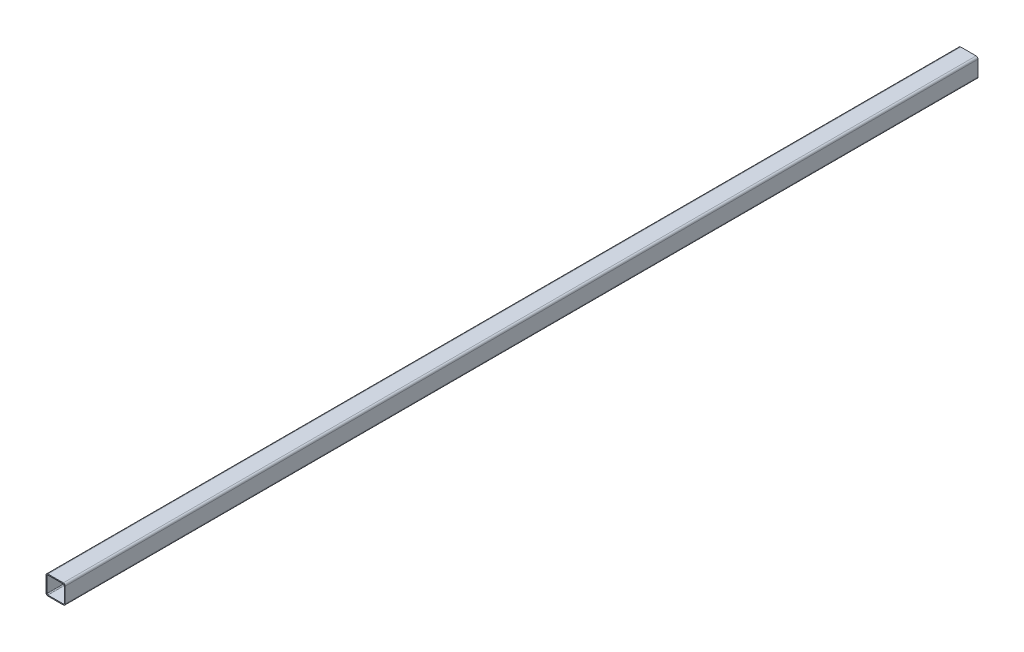
SolidWorks part; units mm, degrees
material "1.4305 (X8CrNiS18-9)"
ref_plane "Ön Düzlem" through (0, 0, 0) normal (0, 0, 1) x (1, 0, 0)
ref_plane "Üst Düzlem" through (0, 0, 0) normal (0, 1, 0) x (1, 0, 0)
ref_plane "Sağ Düzlem" through (0, 0, 0) normal (1, 0, 0) x (0, 0, -1)
sketch "Çizim1" plane through (0, 0, 0) normal (0, 0, 1) x (1, 0, 0)
  line L0 (-18, 16) -> (-18, -16)
  line L1 (-16, 20) -> (16, 20)
  line L2 (-20, 16) -> (-20, -16)
  line L3 (-16, -20) -> (16, -20)
  line L4 (20, 16) -> (20, -16)
  line L5 (-20, 20) -> (20, -20) construction
  line L6 (-20, -20) -> (20, 20) construction
  line L7 (-16, -18) -> (16, -18)
  line L8 (18, 16) -> (18, -16)
  line L9 (-16, 18) -> (16, 18)
  arc A0 (20, -16) -> (16, -20) centre (16, -16) cw
  arc A1 (16, 20) -> (20, 16) centre (16, 16) cw
  arc A2 (-16, 20) -> (-20, 16) centre (-16, 16) ccw
  arc A3 (-20, -16) -> (-16, -20) centre (-16, -16) ccw
  arc A4 (-18, -16) -> (-16, -18) centre (-16, -16) ccw
  arc A5 (18, -16) -> (16, -18) centre (16, -16) cw
  arc A6 (16, 18) -> (18, 16) centre (16, 16) cw
  arc A7 (-16, 18) -> (-18, 16) centre (-16, 16) ccw
  point P0 (0, 0)
  dimension "D3" = 4
  dimension "D1" = 40
  dimension "D2" = 40
  dimension "D4" = 2
extrude "Yükseklik-Ekstrüzyon1" add sketch "Çizim1" along normal blind 1900
sketch "Çizim2" plane through (0, 0, 0) normal (0, 0, -1) x (-1, 0, 0)
  line L0 (-18.8284, 18.8284) -> (18.8284, -18.8284) construction
  arc A0 (-16, 20) -> (-20, 16) centre (-16, 16) ccw construction
  arc A1 (16, -20) -> (20, -16) centre (16, -16) ccw construction
ref_plane "Düzlem1" through (0, 0, 0) normal (0.7071, -0.7071, 0) x (-0.7071, -0.7071, 0)
